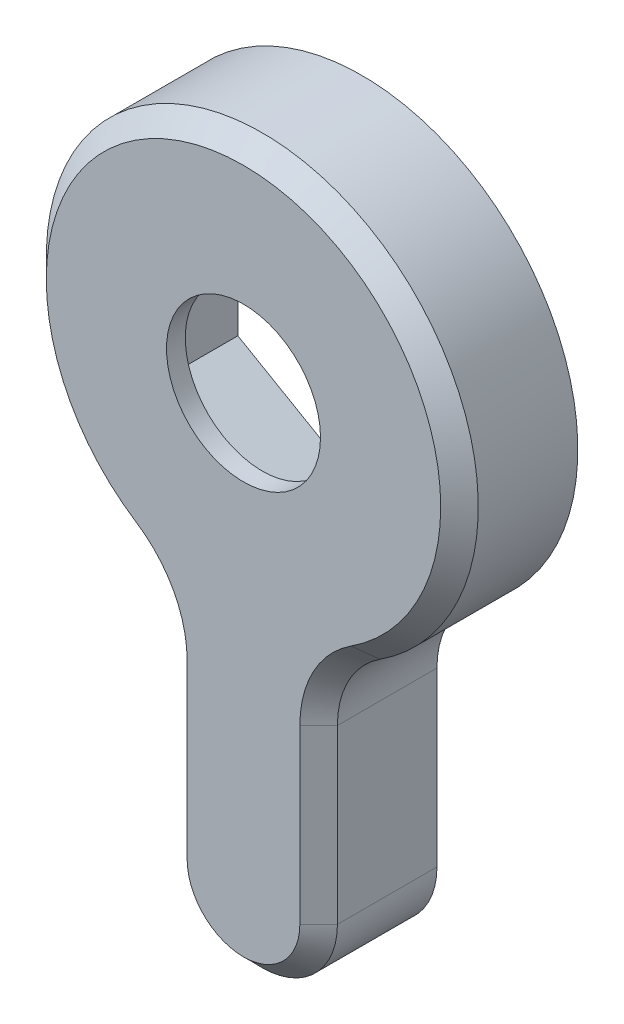
SolidWorks part; units mm, degrees
ref_plane "Front Plane" through (0, 0, 0) normal (0, 0, 1) x (1, 0, 0)
ref_plane "Top Plane" through (0, 0, 0) normal (0, 1, 0) x (1, 0, 0)
ref_plane "Right Plane" through (0, 0, 0) normal (1, 0, 0) x (0, 0, -1)
sketch "Sketch1" plane through (0, 0, 0) normal (0, 0, 1) x (1, 0, 0)
  line L3 (3.25, 5.6292) -> (0, 7.5056) construction
  line L4 (0, 7.621) -> (-6.6, 3.8105)
  line L5 (-6.6, 3.8105) -> (-6.6, -3.8105)
  line L6 (-6.6, -3.8105) -> (0, -7.621)
  line L7 (0, -7.621) -> (6.6, -3.8105)
  line L8 (6.6, -3.8105) -> (6.6, 3.8105)
  line L9 (6.6, 3.8105) -> (0, 7.621)
  circle A1 centre (0, 0) radius 6.6 construction
  circle A2 centre (0, 0) radius 11.5
  circle A3 centre (0, 0) radius 10 construction
  dimension "D2" = 1.5
  dimension "D1" = 0.1
extrude "Boss-Extrude1" add sketch "Sketch1" against normal up to surface (5.3 mm away)
sketch "Sketch2" plane through (0, 0, 0) normal (0, 0, 1) x (1, 0, 0)
  circle A1 centre (0, 0) radius 11.5
  circle A2 centre (0, 0) radius 11.5
  dimension "D1" = 0
extrude "Boss-Extrude2" add sketch "Sketch2" along normal blind 1
sketch "Sketch3" plane through (0, 0, 1) normal (0, 0, 1) x (1, 0, 0)
  line L0 (0, 0) -> (0, -23) construction
  line L1 (4, 0) -> (4, -23)
  line L2 (-4, 0) -> (-4, -23)
  arc A0 (4, 0) -> (-4, 0) centre (0, 0) ccw
  arc A1 (-4, -23) -> (4, -23) centre (0, -23) ccw
  circle A2 centre (0, 0) radius 11.5 construction
  circle A3 centre (0, 0) radius 11.5
  point P3 (0, -11.5)
  dimension "D1" = 8
  dimension "D2" = 23
extrude "Boss-Extrude3" add sketch "Sketch3" against normal up to surface (6.3 mm away) up to face at (-11.5, 0, -5.3)
fillet "Fillet1" radius 5 2 edges at (-4, -10.7819, -2.15) (4, -10.7819, -2.15)
chamfer "Chamfer1" distance 1 angle 45 6 edges at (0, -27, 1) (4, -18.4147, 1) (-4, -18.4147, 1) (4.6048, -11.4457, 1) (-4.6048, -11.4457, 1) (0, 11.5, 1)
sketch "Sketch4" plane through (0, 0, 1) normal (0, 0, 1) x (1, 0, 0)
  circle A0 centre (0, 0) radius 4.1
  dimension "D1" = 8.2
extrude "Cut-Extrude1" cut sketch "Sketch4" against normal up to next
